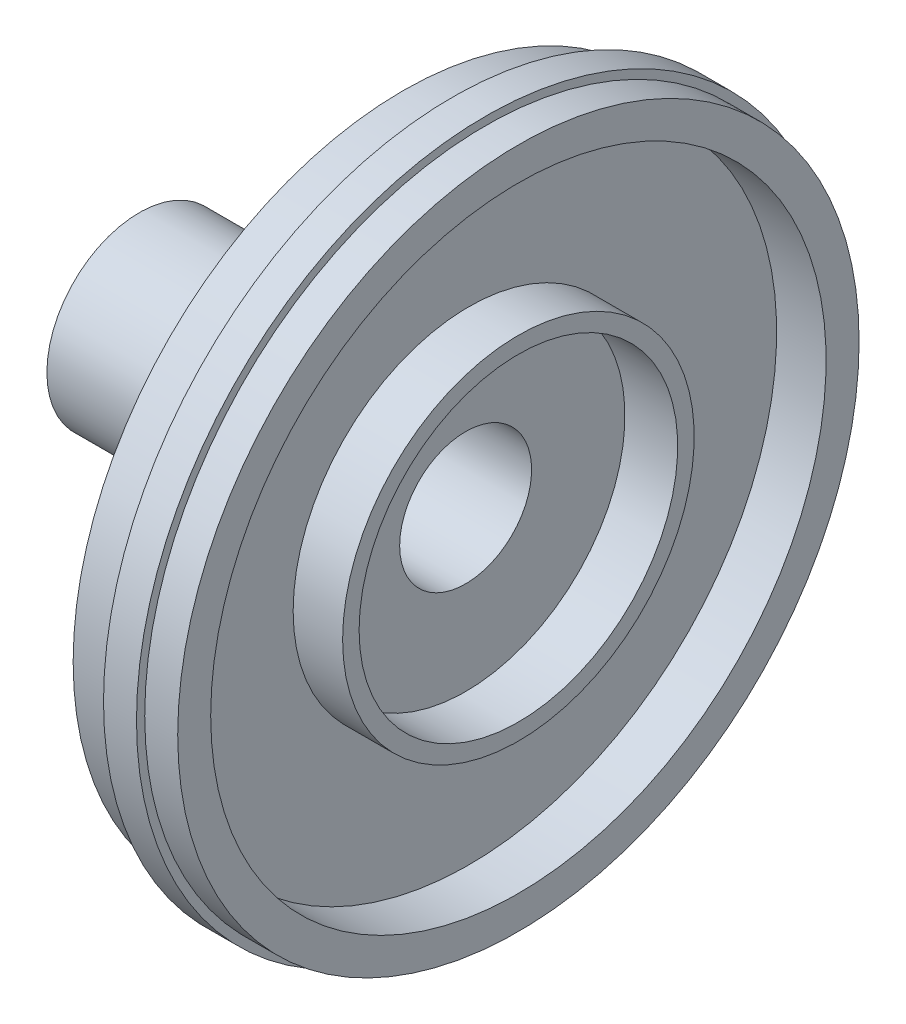
SolidWorks part; units mm, degrees
ref_plane "Front Plane" through (0, 0, 0) normal (0, 0, 1) x (1, 0, 0)
ref_plane "Top Plane" through (0, 0, 0) normal (0, 1, 0) x (1, 0, 0)
ref_plane "Right Plane" through (0, 0, 0) normal (1, 0, 0) x (0, 0, -1)
sketch "Sketch1" plane through (0, 0, 0) normal (0, 0, 1) x (1, 0, 0)
  line L0 (0, 0) -> (36.4998, 0) construction
  line L1 (36.4998, 0) -> (36.4998, 15.3353) construction
  line L2 (0, 0) -> (0, 6.35) construction
  line L3 (0, 6.35) -> (31.4198, 6.35)
  line L4 (31.4198, 6.35) -> (31.4198, 15.3353)
  line L5 (31.4198, 15.3353) -> (36.4998, 15.3353)
  line L6 (36.4998, 15.3353) -> (36.4998, 16.9228)
  line L7 (36.4998, 16.9228) -> (31.7373, 16.9228)
  line L8 (31.7373, 16.9228) -> (31.7373, 29.6227)
  line L9 (31.7373, 29.6227) -> (36.4998, 29.6227)
  line L10 (36.4998, 29.6227) -> (36.4998, 32.7978)
  line L11 (36.4998, 32.7978) -> (33.3248, 32.7978)
  line L12 (33.3248, 32.7978) -> (33.3248, 33.5915)
  line L13 (33.3248, 33.5915) -> (30.1498, 33.5915)
  line L14 (30.1498, 33.5915) -> (30.1498, 31.75)
  line L15 (30.1498, 31.75) -> (25.3873, 31.75)
  line L16 (25.3873, 31.75) -> (25.3873, 28.575)
  line L17 (25.3873, 28.575) -> (30.1498, 28.575)
  line L18 (30.1498, 28.575) -> (30.1498, 19.05)
  line L19 (30.1498, 19.05) -> (26.9748, 19.05)
  line L20 (26.9748, 19.05) -> (26.9748, 9.525)
  line L21 (26.9748, 9.525) -> (19.05, 9.525)
  line L22 (19.05, 9.525) -> (19.05, 8.89)
  line L23 (19.05, 8.89) -> (0, 8.89)
  line L24 (0, 8.89) -> (0, 6.35)
  point P4 (36.4998, 25.1723)
  point P26 (36.4998, 12.1233)
  point P27 (36.4998, 32.7073)
  dimension "D1" = 36.4998
  dimension "D2" = 12.7
  dimension "D3" = 19.05
  dimension "D4" = 17.78
  dimension "D5" = 4.7625
  dimension "D6" = 3.175
  dimension "D7" = 3.175
  dimension "D8" = 4.7625
  dimension "D9" = 67.183
  dimension "D10" = 63.5
  dimension "D11" = 3.175
  dimension "D12" = 1.5875
  dimension "D13" = 3.175
  dimension "D14" = 0.7937
  dimension "D15" = 19.05
  dimension "D16" = 3.175
  dimension "D17" = 9.525
  dimension "D18" = 1.5875
  dimension "D19" = 12.7
  dimension "D20" = 5.08
revolve "Revolve1" add sketch "Sketch1" angle 360 about L0
